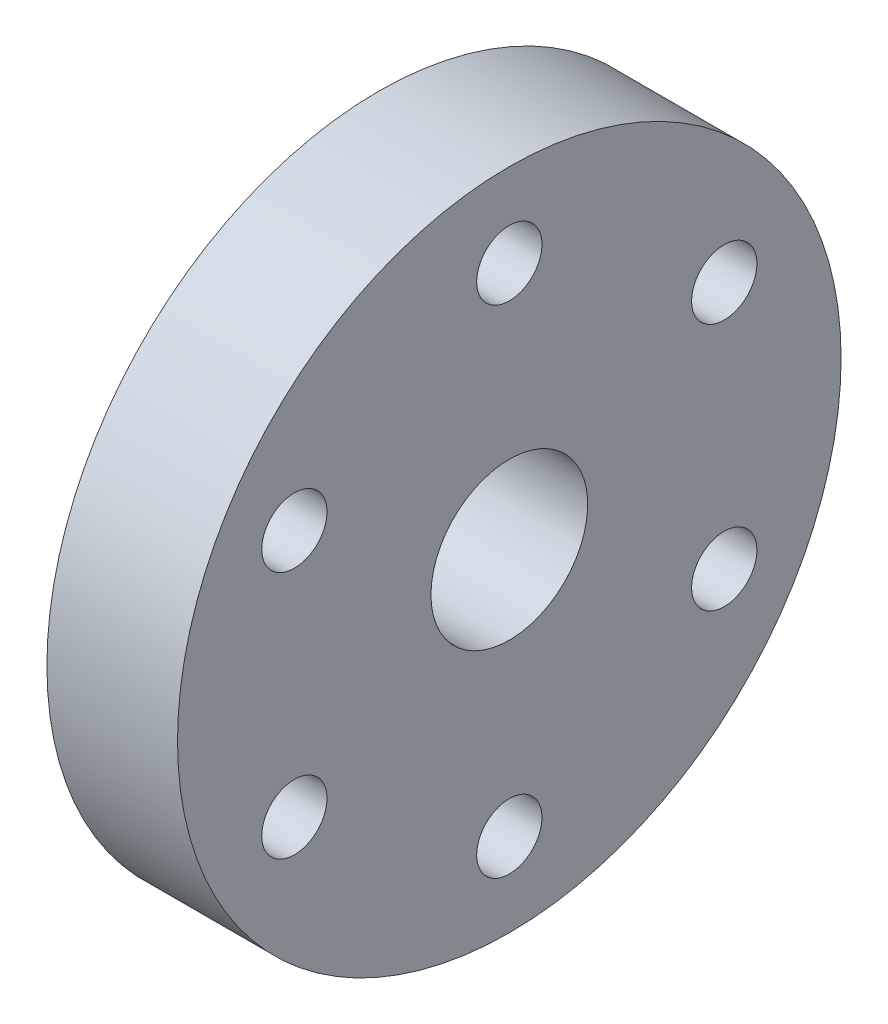
SolidWorks part; units mm, degrees
ref_plane "Front Plane" through (0, 0, 0) normal (0, 0, 1) x (1, 0, 0)
ref_plane "Top Plane" through (0, 0, 0) normal (0, 1, 0) x (1, 0, 0)
ref_plane "Right Plane" through (0, 0, 0) normal (1, 0, 0) x (0, 0, -1)
sketch "Sketch1" plane through (0, 0, 0) normal (0, 0, 1) x (1, 0, 0)
  line L0 (0, 3) -> (0, 6)
  line L1 (0, 6) -> (4.2, 6)
  line L2 (4.2, 6) -> (4.2, 12.7)
  line L3 (4.2, 12.7) -> (9.2, 12.7)
  line L4 (9.2, 12.7) -> (9.2, 3)
  line L5 (9.2, 3) -> (0, 3)
  line L6 (0, 0) -> (9.2, 0) construction
  dimension "D1" = 5
  dimension "D2" = 4.2
  dimension "D3" = 12.7
  dimension "D4" = 6
  dimension "D5" = 3
revolve "Revolve1" add sketch "Sketch1" angle 360 about L6
hole_wizard "Tap Drill for M3x0.5 Tap1" positions "Sketch3" profile "Sketch2" hole size "M3x0.5" standard "ANSI Metric" end condition up to next
sketch "Sketch3" plane through (4.2, 0, 0) normal (-1, 0, 0) x (0, 0, 1)
  point P0 (0, 9.5)
  dimension "D1" = 9.5
sketch "Sketch2" plane through (4.2, 9.5, 0) normal (0, 1, 0) x (0, 0, 1)
  line L0 (0, 0) -> (0, 5.001)
  line L1 (0, 5.001) -> (1.25, 5.001)
  line L2 (1.25, 5.001) -> (1.25, 0)
  line L5 (1.25, 0) -> (0, 0)
  line L11 (0, -6.35) -> (0, 107.95) construction
  dimension "Thru Hole Dia." = 2.5
  dimension "Thru Hole Depth" = 5.001
pattern_circular "CirPattern1" count 6 over 360 about axis through (0, 0, 0) along (1, 0, 0) of "Tap Drill for M3x0.5 Tap1"
